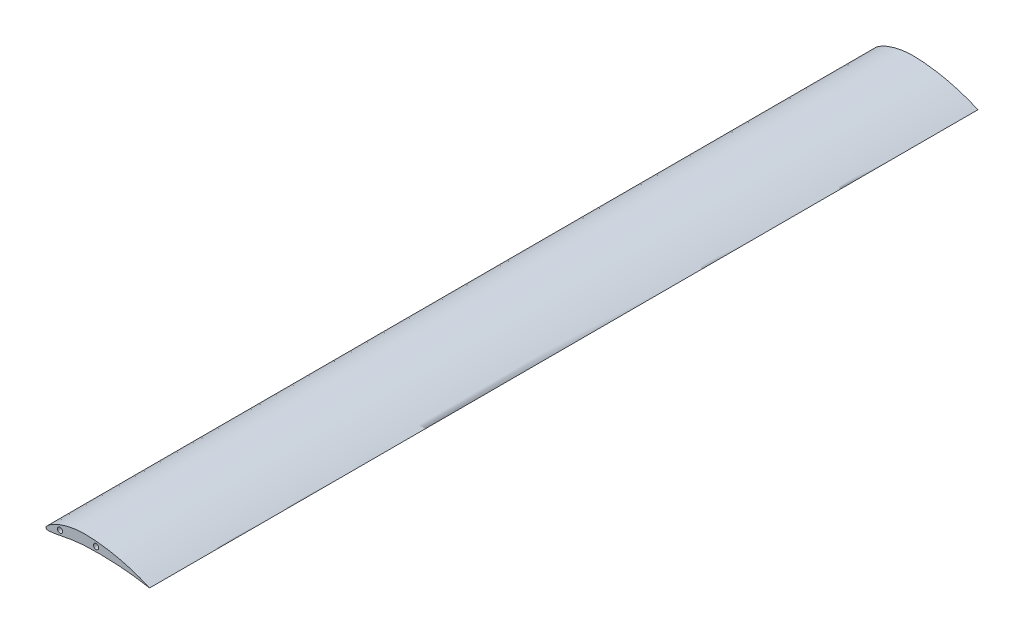
SolidWorks part; units mm, degrees
material "Thornel Mat VMA"
ref_plane "Front Plane" through (0, 0, 0) normal (0, 0, 1) x (1, 0, 0)
ref_plane "Top Plane" through (0, 0, 0) normal (0, 1, 0) x (1, 0, 0)
ref_plane "Right Plane" through (0, 0, 0) normal (1, 0, 0) x (0, 0, -1)
curve "Curve2"
  spline degree 3 poles (126.7243, 0.0562, 0) (127.0672, -0.0201, 0) (126.7388, 0.1047, 0) (126.4748, 0.2306, 0) (125.8171, 0.5041, 0) (125.0013, 0.8517, 0) (123.9159, 1.3031, 0) (122.611, 1.8386, 0) (121.0733, 2.4568, 0) (119.3139, 3.1484, 0) (117.3361, 3.905, 0) (115.1475, 4.7179, 0) (112.7548, 5.577, 0) (110.1664, 6.4722, 0) (107.3911, 7.3926, 0) (104.4387, 8.3281, 0) (101.3196, 9.2676, 0) (98.0451, 10.2005, 0) (94.6272, 11.1163, 0) (91.0787, 12.005, 0) (87.4128, 12.8564, 0) (83.6438, 13.6617, 0) (79.7861, 14.4119, 0) (75.8551, 15.0991, 0) (71.8664, 15.7161, 0) (67.8362, 16.2564, 0) (63.7812, 16.7143, 0) (59.7181, 17.0861, 0) (55.6641, 17.3663, 0) (51.6057, 17.5605, 0) (47.5497, 17.6412, 0) (43.5148, 17.5378, 0) (39.5533, 17.2717, 0) (35.6932, 16.8469, 0) (31.9543, 16.2758, 0) (28.3553, 15.5706, 0) (24.914, 14.7471, 0) (21.6468, 13.8212, 0) (18.5691, 12.8108, 0) (15.6943, 11.7353, 0) (13.0349, 10.6131, 0) (10.6014, 9.464, 0) (8.4029, 8.307, 0) (6.4471, 7.16, 0) (4.7395, 6.0413, 0) (3.285, 4.9663, 0) (2.0861, 3.9494, 0) (1.1439, 3.0025, 0) (0.4567, 2.1341, 0) (0.0222, 1.3465, 0) (-0.1592, 0.6274, 0) (-0.0471, -0.0212, 0) (0.3628, -0.5343, 0) (1.0129, -0.8798, 0) (1.8739, -1.0932, 0) (2.9526, -1.1909, 0) (4.2482, -1.181, 0) (5.7566, -1.0702, 0) (7.471, -0.8664, 0) (9.3833, -0.579, 0) (11.4845, -0.2184, 0) (13.7651, 0.2035, 0) (16.2153, 0.6748, 0) (18.8252, 1.1825, 0) (21.5848, 1.7133, 0) (24.4845, 2.2535, 0) (27.5142, 2.7896, 0) (30.6646, 3.3078, 0) (33.926, 3.7949, 0) (37.2894, 4.2376, 0) (40.7453, 4.6244, 0) (44.2845, 4.9416, 0) (47.9054, 5.1842, 0) (51.6294, 5.3255, 0) (55.4417, 5.4237, 0) (59.3213, 5.496, 0) (63.2232, 5.5314, 0) (67.133, 5.5287, 0) (71.0362, 5.4857, 0) (74.918, 5.4015, 0) (78.7636, 5.2757, 0) (82.558, 5.1098, 0) (86.2861, 4.9056, 0) (89.933, 4.6656, 0) (93.4839, 4.3937, 0) (96.9243, 4.0943, 0) (100.2396, 3.7719, 0) (103.416, 3.4324, 0) (106.4398, 3.0813, 0) (109.298, 2.7248, 0) (111.9781, 2.3688, 0) (114.4682, 2.0195, 0) (116.7573, 1.683, 0) (118.835, 1.3649, 0) (120.6912, 1.0703, 0) (122.3195, 0.8043, 0) (123.7061, 0.5724, 0) (124.8619, 0.3738, 0) (125.7348, 0.2252, 0) (126.4345, 0.0955, 0) (126.7243, 0.0562, 0) (127.0672, -0.0201, 0) (126.7388, 0.1047, 0) knots -0.004489 -0.002 -0.000501 0 0.0005 0.002 0.004491 0.007963 0.0124 0.017783 0.024086 0.031283 0.039342 0.048229 0.057904 0.068328 0.079457 0.091243 0.10364 0.116598 0.130063 0.143985 0.158306 0.172972 0.187927 0.203113 0.218472 0.233945 0.249473 0.264999 0.280462 0.295804 0.311324 0.326707 0.34181 0.356583 0.370972 0.384924 0.398387 0.411307 0.423633 0.435312 0.446295 0.456535 0.465988 0.474613 0.482377 0.489253 0.495224 0.500286 0.504461 0.507812 0.510481 0.512762 0.515043 0.517702 0.521013 0.525104 0.530021 0.535772 0.542341 0.549703 0.557819 0.566648 0.576147 0.586268 0.596965 0.60819 0.619899 0.632047 0.644592 0.657497 0.670724 0.68424 0.698011 0.712098 0.726728 0.741494 0.756341 0.771219 0.786073 0.800848 0.81549 0.829943 0.844153 0.858061 0.871615 0.884758 0.897436 0.909595 0.921182 0.932145 0.942437 0.952008 0.960816 0.968817 0.975974 0.98225 0.987616 0.992043 0.995511 0.998 0.999499 1 1.0005 1.002 1.004491 periodic
sketch "Sketch2" plane through (0, 0, 0) normal (0, 0, 1) x (1, 0, 0)
  spline S0 degree 3 poles (126.7243, 0.0562) (127.0672, -0.0201) (126.7388, 0.1047) (126.4748, 0.2306) (125.8171, 0.5041) (125.0013, 0.8517) (123.9159, 1.3031) (122.611, 1.8386) (121.0733, 2.4568) (119.3139, 3.1484) (117.3361, 3.905) (115.1475, 4.7179) (112.7548, 5.577) (110.1664, 6.4722) (107.3911, 7.3926) (104.4387, 8.3281) (101.3196, 9.2676) (98.0451, 10.2005) (94.6272, 11.1163) (91.0787, 12.005) (87.4128, 12.8564) (83.6438, 13.6617) (79.7861, 14.4119) (75.8551, 15.0991) (71.8664, 15.7161) (67.8362, 16.2564) (63.7812, 16.7143) (59.7181, 17.0861) (55.6641, 17.3663) (51.6057, 17.5605) (47.5497, 17.6412) (43.5148, 17.5378) (39.5533, 17.2717) (35.6932, 16.8469) (31.9543, 16.2758) (28.3553, 15.5706) (24.914, 14.7471) (21.6468, 13.8212) (18.5691, 12.8108) (15.6943, 11.7353) (13.0349, 10.6131) (10.6014, 9.464) (8.4029, 8.307) (6.4471, 7.16) (4.7395, 6.0413) (3.285, 4.9663) (2.0861, 3.9494) (1.1439, 3.0025) (0.4567, 2.1341) (0.0222, 1.3465) (-0.1592, 0.6274) (-0.0471, -0.0212) (0.3628, -0.5343) (1.0129, -0.8798) (1.8739, -1.0932) (2.9526, -1.1909) (4.2482, -1.181) (5.7566, -1.0702) (7.471, -0.8664) (9.3833, -0.579) (11.4845, -0.2184) (13.7651, 0.2035) (16.2153, 0.6748) (18.8252, 1.1825) (21.5848, 1.7133) (24.4845, 2.2535) (27.5142, 2.7896) (30.6646, 3.3078) (33.926, 3.7949) (37.2894, 4.2376) (40.7453, 4.6244) (44.2845, 4.9416) (47.9054, 5.1842) (51.6294, 5.3255) (55.4417, 5.4237) (59.3213, 5.496) (63.2232, 5.5314) (67.133, 5.5287) (71.0362, 5.4857) (74.918, 5.4015) (78.7636, 5.2757) (82.558, 5.1098) (86.2861, 4.9056) (89.933, 4.6656) (93.4839, 4.3937) (96.9243, 4.0943) (100.2396, 3.7719) (103.416, 3.4324) (106.4398, 3.0813) (109.298, 2.7248) (111.9781, 2.3688) (114.4682, 2.0195) (116.7573, 1.683) (118.835, 1.3649) (120.6912, 1.0703) (122.3195, 0.8043) (123.7061, 0.5724) (124.8619, 0.3738) (125.7348, 0.2252) (126.4345, 0.0955) (126.7243, 0.0562) (127.0672, -0.0201) (126.7388, 0.1047) knots -0.004489 -0.002 -0.000501 0 0.0005 0.002 0.004491 0.007963 0.0124 0.017783 0.024086 0.031283 0.039342 0.048229 0.057904 0.068328 0.079457 0.091243 0.10364 0.116598 0.130063 0.143985 0.158306 0.172972 0.187927 0.203113 0.218472 0.233945 0.249473 0.264999 0.280462 0.295804 0.311324 0.326707 0.34181 0.356583 0.370972 0.384924 0.398387 0.411307 0.423633 0.435312 0.446295 0.456535 0.465988 0.474613 0.482377 0.489253 0.495224 0.500286 0.504461 0.507812 0.510481 0.512762 0.515043 0.517702 0.521013 0.525104 0.530021 0.535772 0.542341 0.549703 0.557819 0.566648 0.576147 0.586268 0.596965 0.60819 0.619899 0.632047 0.644592 0.657497 0.670724 0.68424 0.698011 0.712098 0.726728 0.741494 0.756341 0.771219 0.786073 0.800848 0.81549 0.829943 0.844153 0.858061 0.871615 0.884758 0.897436 0.909595 0.921182 0.932145 0.942437 0.952008 0.960816 0.968817 0.975974 0.98225 0.987616 0.992043 0.995511 0.998 0.999499 1 1.0005 1.002 1.004491 only from (127, 0) to (127, 0) construction
  spline S1 degree 3 poles (126.7243, 0.0562) (127.0672, -0.0201) (126.7388, 0.1047) (126.4748, 0.2306) (125.8171, 0.5041) (125.0013, 0.8517) (123.9159, 1.3031) (122.611, 1.8386) (121.0733, 2.4568) (119.3139, 3.1484) (117.3361, 3.905) (115.1475, 4.7179) (112.7548, 5.577) (110.1664, 6.4722) (107.3911, 7.3926) (104.4387, 8.3281) (101.3196, 9.2676) (98.0451, 10.2005) (94.6272, 11.1163) (91.0787, 12.005) (87.4128, 12.8564) (83.6438, 13.6617) (79.7861, 14.4119) (75.8551, 15.0991) (71.8664, 15.7161) (67.8362, 16.2564) (63.7812, 16.7143) (59.7181, 17.0861) (55.6641, 17.3663) (51.6057, 17.5605) (47.5497, 17.6412) (43.5148, 17.5378) (39.5533, 17.2717) (35.6932, 16.8469) (31.9543, 16.2758) (28.3553, 15.5706) (24.914, 14.7471) (21.6468, 13.8212) (18.5691, 12.8108) (15.6943, 11.7353) (13.0349, 10.6131) (10.6014, 9.464) (8.4029, 8.307) (6.4471, 7.16) (4.7395, 6.0413) (3.285, 4.9663) (2.0861, 3.9494) (1.1439, 3.0025) (0.4567, 2.1341) (0.0222, 1.3465) (-0.1592, 0.6274) (-0.0471, -0.0212) (0.3628, -0.5343) (1.0129, -0.8798) (1.8739, -1.0932) (2.9526, -1.1909) (4.2482, -1.181) (5.7566, -1.0702) (7.471, -0.8664) (9.3833, -0.579) (11.4845, -0.2184) (13.7651, 0.2035) (16.2153, 0.6748) (18.8252, 1.1825) (21.5848, 1.7133) (24.4845, 2.2535) (27.5142, 2.7896) (30.6646, 3.3078) (33.926, 3.7949) (37.2894, 4.2376) (40.7453, 4.6244) (44.2845, 4.9416) (47.9054, 5.1842) (51.6294, 5.3255) (55.4417, 5.4237) (59.3213, 5.496) (63.2232, 5.5314) (67.133, 5.5287) (71.0362, 5.4857) (74.918, 5.4015) (78.7636, 5.2757) (82.558, 5.1098) (86.2861, 4.9056) (89.933, 4.6656) (93.4839, 4.3937) (96.9243, 4.0943) (100.2396, 3.7719) (103.416, 3.4324) (106.4398, 3.0813) (109.298, 2.7248) (111.9781, 2.3688) (114.4682, 2.0195) (116.7573, 1.683) (118.835, 1.3649) (120.6912, 1.0703) (122.3195, 0.8043) (123.7061, 0.5724) (124.8619, 0.3738) (125.7348, 0.2252) (126.4345, 0.0955) (126.7243, 0.0562) (127.0672, -0.0201) (126.7388, 0.1047) knots -0.004489 -0.002 -0.000501 0 0.0005 0.002 0.004491 0.007963 0.0124 0.017783 0.024086 0.031283 0.039342 0.048229 0.057904 0.068328 0.079457 0.091243 0.10364 0.116598 0.130063 0.143985 0.158306 0.172972 0.187927 0.203113 0.218472 0.233945 0.249473 0.264999 0.280462 0.295804 0.311324 0.326707 0.34181 0.356583 0.370972 0.384924 0.398387 0.411307 0.423633 0.435312 0.446295 0.456535 0.465988 0.474613 0.482377 0.489253 0.495224 0.500286 0.504461 0.507812 0.510481 0.512762 0.515043 0.517702 0.521013 0.525104 0.530021 0.535772 0.542341 0.549703 0.557819 0.566648 0.576147 0.586268 0.596965 0.60819 0.619899 0.632047 0.644592 0.657497 0.670724 0.68424 0.698011 0.712098 0.726728 0.741494 0.756341 0.771219 0.786073 0.800848 0.81549 0.829943 0.844153 0.858061 0.871615 0.884758 0.897436 0.909595 0.921182 0.932145 0.942437 0.952008 0.960816 0.968817 0.975974 0.98225 0.987616 0.992043 0.995511 0.998 0.999499 1 1.0005 1.002 1.004491 only from (127, 0) to (127, 0)
extrude "Boss-Extrude1" add sketch "Sketch2" along normal blind 1016
sketch "Sketch3" plane through (0, 0, 1016) normal (0, 0, 1) x (1, 0, 0)
  line L0 (17.1183, 6.3505) -> (61.3032, 11.1985) construction
  line L1 (60.7808, 5.5074) -> (61.8255, 16.8895) construction
  line L2 (15.0324, 11.4461) -> (19.2042, 1.2548) construction
  circle A0 centre (17.1183, 6.3505) radius 3.175
  circle A1 centre (61.3032, 11.1985) radius 3.175
  spline S1 degree 3 poles (126.7243, 0.0562) (127.0672, -0.0201) (126.7388, 0.1047) (126.4748, 0.2306) (125.8171, 0.5041) (125.0013, 0.8517) (123.9159, 1.3031) (122.611, 1.8386) (121.0733, 2.4568) (119.3139, 3.1484) (117.3361, 3.905) (115.1475, 4.7179) (112.7548, 5.577) (110.1664, 6.4722) (107.3911, 7.3926) (104.4387, 8.3281) (101.3196, 9.2676) (98.0451, 10.2005) (94.6272, 11.1163) (91.0787, 12.005) (87.4128, 12.8564) (83.6438, 13.6617) (79.7861, 14.4119) (75.8551, 15.0991) (71.8664, 15.7161) (67.8362, 16.2564) (63.7812, 16.7143) (59.7181, 17.0861) (55.6641, 17.3663) (51.6057, 17.5605) (47.5497, 17.6412) (43.5148, 17.5378) (39.5533, 17.2717) (35.6932, 16.8469) (31.9543, 16.2758) (28.3553, 15.5706) (24.914, 14.7471) (21.6468, 13.8212) (18.5691, 12.8108) (15.6943, 11.7353) (13.0349, 10.6131) (10.6014, 9.464) (8.4029, 8.307) (6.4471, 7.16) (4.7395, 6.0413) (3.285, 4.9663) (2.0861, 3.9494) (1.1439, 3.0025) (0.4567, 2.1341) (0.0222, 1.3465) (-0.1592, 0.6274) (-0.0471, -0.0212) (0.3628, -0.5343) (1.0129, -0.8798) (1.8739, -1.0932) (2.9526, -1.1909) (4.2482, -1.181) (5.7566, -1.0702) (7.471, -0.8664) (9.3833, -0.579) (11.4845, -0.2184) (13.7651, 0.2035) (16.2153, 0.6748) (18.8252, 1.1825) (21.5848, 1.7133) (24.4845, 2.2535) (27.5142, 2.7896) (30.6646, 3.3078) (33.926, 3.7949) (37.2894, 4.2376) (40.7453, 4.6244) (44.2845, 4.9416) (47.9054, 5.1842) (51.6294, 5.3255) (55.4417, 5.4237) (59.3213, 5.496) (63.2232, 5.5314) (67.133, 5.5287) (71.0362, 5.4857) (74.918, 5.4015) (78.7636, 5.2757) (82.558, 5.1098) (86.2861, 4.9056) (89.933, 4.6656) (93.4839, 4.3937) (96.9243, 4.0943) (100.2396, 3.7719) (103.416, 3.4324) (106.4398, 3.0813) (109.298, 2.7248) (111.9781, 2.3688) (114.4682, 2.0195) (116.7573, 1.683) (118.835, 1.3649) (120.6912, 1.0703) (122.3195, 0.8043) (123.7061, 0.5724) (124.8619, 0.3738) (125.7348, 0.2252) (126.4345, 0.0955) (126.7243, 0.0562) (127.0672, -0.0201) (126.7388, 0.1047) knots -0.004489 -0.002 -0.000501 0 0.0005 0.002 0.004491 0.007963 0.0124 0.017783 0.024086 0.031283 0.039342 0.048229 0.057904 0.068328 0.079457 0.091243 0.10364 0.116598 0.130063 0.143985 0.158306 0.172972 0.187927 0.203113 0.218472 0.233945 0.249473 0.264999 0.280462 0.295804 0.311324 0.326707 0.34181 0.356583 0.370972 0.384924 0.398387 0.411307 0.423633 0.435312 0.446295 0.456535 0.465988 0.474613 0.482377 0.489253 0.495224 0.500286 0.504461 0.507812 0.510481 0.512762 0.515043 0.517702 0.521013 0.525104 0.530021 0.535772 0.542341 0.549703 0.557819 0.566648 0.576147 0.586268 0.596965 0.60819 0.619899 0.632047 0.644592 0.657497 0.670724 0.68424 0.698011 0.712098 0.726728 0.741494 0.756341 0.771219 0.786073 0.800848 0.81549 0.829943 0.844153 0.858061 0.871615 0.884758 0.897436 0.909595 0.921182 0.932145 0.942437 0.952008 0.960816 0.968817 0.975974 0.98225 0.987616 0.992043 0.995511 0.998 0.999499 1 1.0005 1.002 1.004491 only from (127, 0) to (127, 0) construction
  dimension "D1" = 6.35
  dimension "D2" = 6.35
  dimension "D3" = 11.43
  dimension "D4" = 44.45
extrude "Cut-Extrude1" cut sketch "Sketch3" against normal through all
